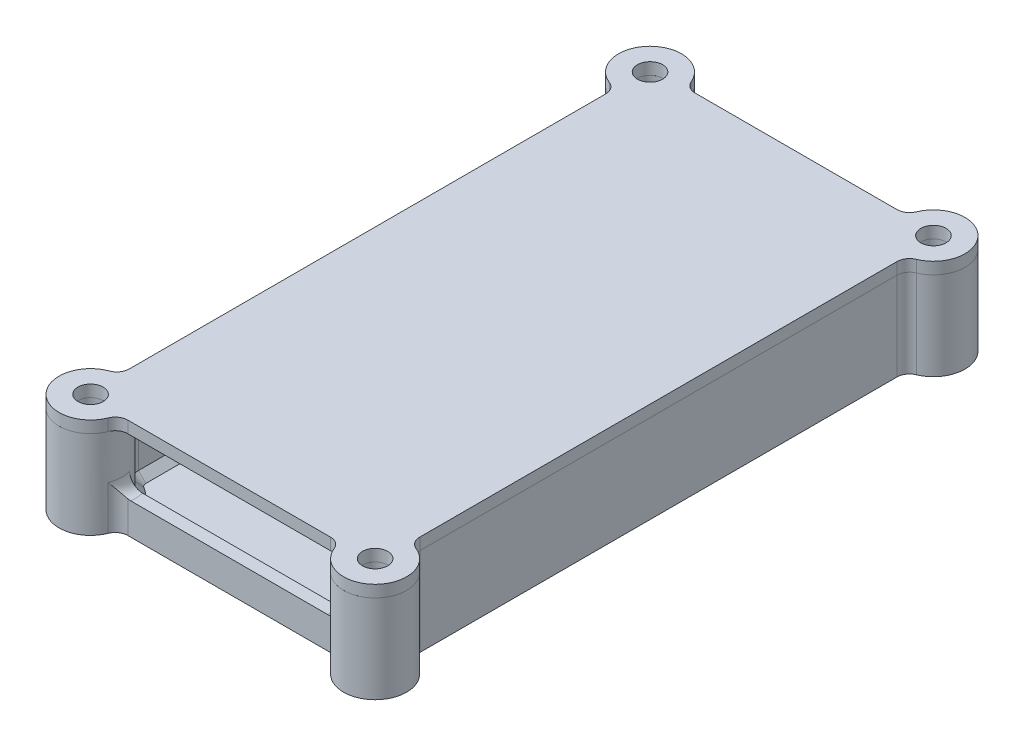
SolidWorks part; units mm, degrees
material "Nylon 101"
ref_plane "Front Plane" through (0, 0, 0) normal (0, 0, 1) x (1, 0, 0)
ref_plane "Top Plane" through (0, 0, 0) normal (0, 1, 0) x (1, 0, 0)
ref_plane "Right Plane" through (0, 0, 0) normal (1, 0, 0) x (0, 0, -1)
sketch "Sketch1" plane through (0, 0, 0) normal (0, 1, 0) x (1, 0, 0)
  line L0 (0, 76.6523) -> (0, -58.1633) construction
  line L5 (-26.67, -25.4) -> (-1.27, -25.4)
  line L6 (-26.67, -25.4) -> (-26.67, 25.4)
  line L7 (-26.67, 25.4) -> (-1.27, 25.4)
  line L8 (-1.27, -25.4) -> (-1.27, 25.4)
  line L17 (-29.21, 27.94) -> (-29.21, -27.94)
  line L18 (-29.21, -27.94) -> (29.4349, -27.94)
  line L19 (29.4349, -27.94) -> (29.4349, 27.94)
  line L20 (29.4349, 27.94) -> (-29.21, 27.94)
  line L21 (26.67, 25.4) -> (1.27, 25.4)
  line L22 (1.27, -25.4) -> (1.27, 25.4)
  line L23 (26.67, -25.4) -> (1.27, -25.4)
  line L24 (26.67, -25.4) -> (26.67, 25.4)
  line L33 (-29.21, 27.94) -> (29.4349, 27.94)
  line L34 (-29.21, -27.94) -> (29.4349, -27.94)
  line L35 (-29.21, -27.94) -> (-29.21, -38.6473)
  line L36 (-29.21, -27.94) -> (29.4349, -27.94)
  line L37 (-29.21, -45.72) -> (-26.2624, -45.72)
  line L38 (29.4349, -27.94) -> (29.4349, -38.6698)
  line L39 (-26.67, -27.94) -> (26.8949, -27.94)
  line L42 (-29.21, 0) -> (29.4349, 0) construction
  line L43 (-26.67, -27.94) -> (-26.67, -38.9562)
  line L44 (-22.6003, -43.18) -> (22.6003, -43.18)
  line L45 (26.8949, -27.94) -> (26.8949, -38.8853) construction
  line L46 (26.7789, 65.924) -> (29.4349, 68.58) construction
  line L47 (-26.67, 27.94) -> (26.67, 27.94)
  line L48 (-29.21, 27.94) -> (29.4349, 27.94)
  line L49 (-26.67, 27.94) -> (-26.67, 61.6625)
  line L54 (-26.67, -25.4) -> (-26.67, -27.94)
  line L55 (26.8949, -27.94) -> (26.67, -25.4) construction
  line L56 (26.67, 25.4) -> (26.67, 27.94)
  line L57 (-26.67, 25.4) -> (-26.67, 27.94)
  line L58 (-1.27, 25.4) -> (1.27, 25.4)
  line L59 (1.27, -25.4) -> (-1.27, -25.4)
  line L60 (-22.4513, 66.04) -> (22.4513, 66.04)
  line L61 (26.67, 27.94) -> (26.67, 61.6625)
  line L62 (-29.21, 27.94) -> (29.4349, 27.94)
  line L63 (-29.21, 27.94) -> (-29.21, 61.4019)
  line L64 (-29.21, 68.58) -> (-26.185, 68.58)
  line L65 (29.4349, 27.94) -> (29.4349, 61.4286)
  line L66 (26.8949, -43.18) -> (29.4349, -45.72) construction
  line L67 (-22.2835, 68.58) -> (22.2835, 68.58)
  line L68 (-29.21, 65.2607) -> (-29.21, 68.58)
  line L69 (26.185, 68.58) -> (29.4349, 68.58)
  line L70 (29.4349, 65.3301) -> (29.4349, 68.58)
  line L71 (26.2624, -45.72) -> (29.4349, -45.72)
  line L72 (29.4349, -42.5474) -> (29.4349, -45.72)
  line L73 (-22.3847, -45.72) -> (22.3847, -45.72)
  line L74 (-29.21, -42.4896) -> (-29.21, -45.72)
  line L75 (22.4513, 66.04) -> (26.67, 66.04) construction
  line L76 (26.67, 66.04) -> (26.67, 61.6625) construction
  line L77 (26.8949, -38.8853) -> (26.8949, -43.18) construction
  line L78 (26.8949, -43.18) -> (22.6003, -43.18) construction
  line L79 (26.67, -25.4) -> (26.67, -43.4375)
  circle A0 centre (-23.368, -17.78) radius 1.4605
  circle A1 centre (-4.6736, 16.637) radius 1.4605
  circle A2 centre (23.2664, 16.637) radius 1.4605
  circle A3 centre (4.572, -17.78) radius 1.4605
  circle A4 centre (28.575, 67.7201) radius 2.54
  circle A5 centre (-28.575, 67.7201) radius 2.54
  circle A6 centre (28.691, -44.9761) radius 2.54
  circle A7 centre (-28.691, -44.9761) radius 2.54
  circle A8 centre (28.575, 67.7201) radius 6.35
  circle A9 centre (-28.575, 67.7201) radius 6.35
  circle A10 centre (-28.691, -44.9761) radius 6.35
  circle A11 centre (28.691, -44.9761) radius 6.35
  point P0 (0, 0)
  point P1 (-26.67, 0)
  point P21 (13.97, -25.4)
  point P22 (-1.27, 0)
  point P23 (1.27, 0)
  dimension "D15" = 2.921
  dimension "D22" = 5.08
  dimension "D23" = 12.7
  dimension "D4" = 57.15
  dimension "D2" = 50.8
  dimension "D3" = 25.4
  dimension "D5" = 2.54
  dimension "D6" = 2.54
  dimension "D7" = 2.54
  dimension "D8" = 2.54
  dimension "D9" = 2.54
  dimension "D10" = 114.3
  dimension "D11" = 2.54
  dimension "D12" = 2.54
  dimension "D13" = 7.62
  dimension "D14" = 3.302
  dimension "D16" = 3.302
  dimension "D17" = 34.417
  dimension "D18" = 18.6944
  dimension "D19" = 18.6944
  dimension "D20" = 2.54
  dimension "D21" = 38.1
  dimension "D27" = 45
  dimension "D24" = 3.81
  dimension "D25" = 3.81
  dimension "D26" = 3.81
extrude "Boss-Extrude1" add sketch "Sketch1" along normal blind 17.78 contours A10 A7 | L35 A10 L43 L18 | L6 L57 L20 L17 L18 L54 | L56 L24 L55 L18 L19 L20 | A11 L38 L18 L45 | A11 A6 | L49 A9 L63 L20 | A8 L61 L20 L65 | A9 A5 | L67 A9 L60 A8 | A8 A4 | L59 L22 L58 L8
sketch "Sketch25" plane through (0, 0, 0) normal (0, 1, 0) x (1, 0, 0)
  line L0 (26.8949, -43.18) -> (22.6003, -43.18) construction
  line L1 (26.8949, -38.8853) -> (26.8949, -43.18) construction
  line L2 (26.8949, -43.18) -> (29.4349, -45.72) construction
  line L3 (29.4349, -42.5474) -> (29.4349, -45.72) construction
  line L4 (26.2624, -45.72) -> (29.4349, -45.72) construction
  line L5 (29.4349, -27.94) -> (29.4349, -38.6698) construction
  line L6 (26.8949, -27.94) -> (26.8949, -38.8853) construction
  line L7 (-29.21, -45.72) -> (-26.2624, -45.72) construction
  line L8 (-29.21, -42.4896) -> (-29.21, -45.72) construction
  line L9 (-29.21, -27.94) -> (-29.21, -38.6473) construction
  line L10 (-26.67, -27.94) -> (-26.67, -38.9562) construction
  line L11 (-22.3847, -45.72) -> (22.3847, -45.72) construction
  line L12 (-22.6003, -43.18) -> (22.6003, -43.18) construction
  line L13 (-26.67, -25.4) -> (-1.27, -25.4) construction
  line L14 (26.67, -25.4) -> (1.27, -25.4) construction
  line L15 (-29.21, -27.94) -> (29.4349, -27.94) construction
  line L16 (-29.21, 0) -> (29.4349, 0) construction
  line L17 (-26.67, -25.4) -> (-26.67, 25.4) construction
  line L18 (-1.27, -25.4) -> (-1.27, 25.4) construction
  line L19 (1.27, -25.4) -> (1.27, 25.4) construction
  line L20 (26.67, 25.4) -> (26.67, 27.94) construction
  line L21 (26.67, -25.4) -> (26.67, 25.4) construction
  line L22 (29.4349, -27.94) -> (29.4349, 27.94) construction
  line L23 (26.67, 25.4) -> (1.27, 25.4) construction
  line L24 (-29.21, 27.94) -> (-29.21, -27.94) construction
  line L25 (-26.67, 25.4) -> (-26.67, 27.94) construction
  line L26 (-26.67, 25.4) -> (-1.27, 25.4) construction
  line L27 (29.4349, 27.94) -> (-29.21, 27.94) construction
  line L28 (-29.21, 27.94) -> (-29.21, 61.4019) construction
  line L29 (-26.67, 27.94) -> (-26.67, 61.6625) construction
  line L30 (26.67, 66.04) -> (26.67, 61.6625) construction
  line L31 (22.4513, 66.04) -> (26.67, 66.04) construction
  line L32 (26.67, 27.94) -> (26.67, 61.6625) construction
  line L33 (29.4349, 27.94) -> (29.4349, 61.4286) construction
  line L34 (26.185, 68.58) -> (29.4349, 68.58) construction
  line L35 (29.4349, 65.3301) -> (29.4349, 68.58) construction
  line L36 (26.7789, 65.924) -> (29.4349, 68.58) construction
  line L37 (0, 76.6523) -> (0, -58.1633) construction
  line L38 (-22.4513, 66.04) -> (22.4513, 66.04) construction
  line L39 (-22.2835, 68.58) -> (22.2835, 68.58) construction
  line L40 (-29.21, 68.58) -> (-26.185, 68.58) construction
  line L41 (-29.21, 65.2607) -> (-29.21, 68.58) construction
  line L42 (26.8949, -43.18) -> (22.6003, -43.18) construction
  line L43 (26.8949, -38.8853) -> (26.8949, -43.18) construction
  line L44 (26.8949, -43.18) -> (29.4349, -45.72) construction
  line L45 (29.4349, -42.5474) -> (29.4349, -45.72)
  line L46 (26.2624, -45.72) -> (29.4349, -45.72)
  line L47 (29.4349, -27.94) -> (29.4349, -38.6698)
  line L48 (26.8949, -27.94) -> (26.8949, -38.8853)
  line L49 (-29.21, -45.72) -> (-26.2624, -45.72)
  line L50 (-29.21, -42.4896) -> (-29.21, -45.72)
  line L51 (-29.21, -27.94) -> (-29.21, -38.6473)
  line L52 (-26.67, -27.94) -> (-26.67, -38.9562)
  line L53 (-22.3847, -45.72) -> (22.3847, -45.72)
  line L54 (-22.6003, -43.18) -> (22.6003, -43.18)
  line L55 (-26.67, -25.4) -> (-1.27, -25.4)
  line L56 (26.67, -25.4) -> (1.27, -25.4)
  line L57 (-29.21, -27.94) -> (29.4349, -27.94)
  line L58 (-29.21, 0) -> (29.4349, 0) construction
  line L59 (-26.67, -25.4) -> (-26.67, 25.4)
  line L60 (-1.27, -25.4) -> (-1.27, 25.4)
  line L61 (1.27, -25.4) -> (1.27, 25.4)
  line L62 (26.67, 25.4) -> (26.67, 27.94)
  line L63 (26.67, -25.4) -> (26.67, 25.4)
  line L64 (29.4349, -27.94) -> (29.4349, 27.94)
  line L65 (26.67, 25.4) -> (1.27, 25.4)
  line L66 (-29.21, 27.94) -> (-29.21, -27.94)
  line L67 (-26.67, 25.4) -> (-26.67, 27.94)
  line L68 (-26.67, 25.4) -> (-1.27, 25.4)
  line L69 (29.4349, 27.94) -> (-29.21, 27.94)
  line L70 (-29.21, 27.94) -> (-29.21, 61.4019)
  line L71 (-26.67, 27.94) -> (-26.67, 61.6625)
  line L72 (26.67, 66.04) -> (26.67, 61.6625) construction
  line L73 (22.4513, 66.04) -> (26.67, 66.04) construction
  line L74 (26.67, 27.94) -> (26.67, 61.6625)
  line L75 (29.4349, 27.94) -> (29.4349, 61.4286)
  line L76 (26.185, 68.58) -> (29.4349, 68.58) construction
  line L77 (29.4349, 65.3301) -> (29.4349, 68.58) construction
  line L78 (26.7789, 65.924) -> (29.4349, 68.58) construction
  line L79 (0, 76.6523) -> (0, -58.1633) construction
  line L80 (-22.4513, 66.04) -> (22.4513, 66.04)
  line L81 (-22.2835, 68.58) -> (22.2835, 68.58)
  line L82 (-29.21, 68.58) -> (-26.185, 68.58)
  line L83 (-29.21, 65.2607) -> (-29.21, 68.58)
  circle A0 centre (28.691, -44.9761) radius 2.54 construction
  circle A1 centre (28.691, -44.9761) radius 6.35 construction
  circle A2 centre (-28.691, -44.9761) radius 2.54 construction
  circle A3 centre (-28.691, -44.9761) radius 6.35 construction
  circle A4 centre (23.2664, 16.637) radius 1.4605 construction
  circle A5 centre (-23.368, -17.78) radius 1.4605 construction
  circle A6 centre (-4.6736, 16.637) radius 1.4605 construction
  circle A7 centre (28.575, 67.7201) radius 2.54 construction
  circle A8 centre (28.575, 67.7201) radius 6.35 construction
  circle A9 centre (-28.575, 67.7201) radius 6.35 construction
  circle A10 centre (28.691, -44.9761) radius 2.54
  circle A11 centre (28.691, -44.9761) radius 6.35
  circle A12 centre (-28.691, -44.9761) radius 2.54
  circle A13 centre (-28.691, -44.9761) radius 6.35
  circle A14 centre (23.2664, 16.637) radius 1.4605
  circle A15 centre (-23.368, -17.78) radius 1.4605
  circle A16 centre (-4.6736, 16.637) radius 1.4605
  circle A17 centre (28.575, 67.7201) radius 2.54
  circle A18 centre (28.575, 67.7201) radius 6.35
  circle A19 centre (-28.575, 67.7201) radius 6.35
  circle A20 centre (4.572, -17.78) radius 1.4605 construction
  circle A21 centre (-28.575, 67.7201) radius 2.54 construction
  circle A22 centre (4.572, -17.78) radius 1.4605
  circle A23 centre (-28.575, 67.7201) radius 2.54
  point P0 (-26.67, 61.6625)
sketch "Sketch16" plane through (0, 0, 0) normal (0, 1, 0) x (1, 0, 0)
  line L0 (0, 63.9928) -> (0, -58.1633) construction
  line L5 (-26.67, -25.4) -> (-1.27, -25.4)
  line L6 (-26.67, -25.4) -> (-26.67, 25.4)
  line L7 (-26.67, 25.4) -> (-1.27, 25.4)
  line L8 (-1.27, -25.4) -> (-1.27, 25.4)
  line L17 (-29.21, 27.94) -> (-29.21, -27.94)
  line L18 (-29.21, -27.94) -> (29.21, -27.94)
  line L19 (29.21, -27.94) -> (29.21, 27.94)
  line L20 (29.21, 27.94) -> (-29.21, 27.94)
  line L21 (26.67, 25.4) -> (1.27, 25.4)
  line L22 (1.27, -25.4) -> (1.27, 25.4)
  line L23 (26.67, -25.4) -> (1.27, -25.4)
  line L24 (26.67, -25.4) -> (26.67, 25.4)
  line L33 (-29.21, 27.94) -> (29.21, 27.94)
  line L34 (-29.21, -27.94) -> (29.21, -27.94)
  line L35 (-29.21, -27.94) -> (-29.21, -43.18)
  line L36 (-29.21, -27.94) -> (29.21, -27.94)
  line L37 (-29.21, -43.18) -> (29.21, -43.18)
  line L38 (29.21, -27.94) -> (29.21, -43.18)
  line L39 (-26.67, -27.94) -> (26.67, -27.94)
  line L42 (-29.21, 0) -> (29.21, 0) construction
  line L43 (-26.67, -27.94) -> (-26.67, -40.64)
  line L44 (-26.67, -40.64) -> (26.67, -40.64)
  line L45 (26.67, -27.94) -> (26.67, -40.64)
  line L46 (-29.21, 43.18) -> (29.21, 43.18)
  line L47 (29.21, 27.94) -> (29.21, 43.18)
  line L48 (-29.21, 27.94) -> (29.21, 27.94)
  line L49 (-29.21, 27.94) -> (-29.21, 43.18)
  line L50 (-26.67, 40.64) -> (26.67, 40.64)
  line L51 (26.67, 27.94) -> (26.67, 40.64)
  line L52 (-26.67, 27.94) -> (26.67, 27.94)
  line L53 (-26.67, 27.94) -> (-26.67, 40.64)
  line L54 (-26.67, -25.4) -> (-26.67, -27.94)
  line L55 (26.67, -27.94) -> (26.67, -25.4)
  line L56 (26.67, 25.4) -> (26.67, 27.94)
  line L57 (-26.67, 25.4) -> (-26.67, 27.94)
  line L58 (-1.27, 25.4) -> (1.27, 25.4)
  line L59 (1.27, -25.4) -> (-1.27, -25.4)
  circle A0 centre (-23.368, -17.78) radius 1.4605
  circle A1 centre (-4.6736, 16.637) radius 1.4605
  circle A2 centre (23.2664, 16.637) radius 1.4605
  circle A3 centre (4.572, -17.78) radius 1.4605
  point P0 (0, 0)
  point P1 (-26.67, 0)
  point P19 (26.67, 0)
  point P21 (13.97, -25.4)
  point P22 (-1.27, 0)
  point P23 (1.27, 0)
  point P44 (0, -1.5571)
  dimension "D15" = 2.921
  dimension "D2" = 50.8
  dimension "D3" = 25.4
  dimension "D4" = 2.54
  dimension "D5" = 2.54
  dimension "D6" = 2.54
  dimension "D7" = 2.54
  dimension "D8" = 2.54
  dimension "D9" = 2.54
  dimension "D10" = 12.7
  dimension "D11" = 2.54
  dimension "D12" = 2.54
  dimension "D13" = 7.62
  dimension "D14" = 3.302
  dimension "D16" = 3.302
  dimension "D17" = 34.417
  dimension "D18" = 18.6944
  dimension "D19" = 18.6944
sketch "Sketch17" plane through (0, 0, 0) normal (0, 1, 0) x (1, 0, 0)
  line L0 (0, 63.9928) -> (0, -58.1633) construction
  line L5 (-26.67, -25.4) -> (-1.27, -25.4)
  line L6 (-26.67, -25.4) -> (-26.67, 25.4)
  line L7 (-26.67, 25.4) -> (-1.27, 25.4)
  line L8 (-1.27, -25.4) -> (-1.27, 25.4)
  line L17 (-29.21, 27.94) -> (-29.21, -27.94)
  line L18 (-29.21, -27.94) -> (29.21, -27.94)
  line L19 (29.21, -27.94) -> (29.21, 27.94)
  line L20 (29.21, 27.94) -> (-29.21, 27.94)
  line L21 (26.67, 25.4) -> (1.27, 25.4)
  line L22 (1.27, -25.4) -> (1.27, 25.4)
  line L23 (26.67, -25.4) -> (1.27, -25.4)
  line L24 (26.67, -25.4) -> (26.67, 25.4)
  line L33 (-29.21, 27.94) -> (29.21, 27.94)
  line L34 (-29.21, -27.94) -> (29.21, -27.94)
  line L35 (-29.21, -27.94) -> (-29.21, -43.18)
  line L36 (-29.21, -27.94) -> (29.21, -27.94)
  line L37 (-29.21, -43.18) -> (29.21, -43.18)
  line L38 (29.21, -27.94) -> (29.21, -43.18)
  line L39 (-26.67, -27.94) -> (26.67, -27.94)
  line L42 (-29.21, 0) -> (29.21, 0) construction
  line L43 (-26.67, -27.94) -> (-26.67, -40.64)
  line L44 (-26.67, -40.64) -> (26.67, -40.64)
  line L45 (26.67, -27.94) -> (26.67, -40.64)
  line L46 (-29.21, 43.18) -> (29.21, 43.18)
  line L47 (29.21, 27.94) -> (29.21, 43.18)
  line L48 (-29.21, 27.94) -> (29.21, 27.94)
  line L49 (-29.21, 27.94) -> (-29.21, 43.18)
  line L50 (-26.67, 40.64) -> (26.67, 40.64)
  line L51 (26.67, 27.94) -> (26.67, 40.64)
  line L52 (-26.67, 27.94) -> (26.67, 27.94)
  line L53 (-26.67, 27.94) -> (-26.67, 40.64)
  line L54 (-26.67, -25.4) -> (-26.67, -27.94)
  line L55 (26.67, -27.94) -> (26.67, -25.4)
  line L56 (26.67, 25.4) -> (26.67, 27.94)
  line L57 (-26.67, 25.4) -> (-26.67, 27.94)
  line L58 (-1.27, 25.4) -> (1.27, 25.4)
  line L59 (1.27, -25.4) -> (-1.27, -25.4)
  circle A0 centre (-23.368, -17.78) radius 1.4605
  circle A1 centre (-4.6736, 16.637) radius 1.4605
  circle A2 centre (23.622, 16.637) radius 1.4605
  circle A3 centre (4.572, -17.78) radius 1.4605
  point P0 (0, 0)
  point P1 (-26.67, 0)
  point P19 (26.67, 0)
  point P21 (13.97, -25.4)
  point P22 (-1.27, 0)
  point P23 (1.27, 0)
  dimension "D15" = 2.921
  dimension "D2" = 50.8
  dimension "D3" = 25.4
  dimension "D4" = 2.54
  dimension "D5" = 2.54
  dimension "D6" = 2.54
  dimension "D7" = 2.54
  dimension "D8" = 2.54
  dimension "D9" = 2.54
  dimension "D10" = 12.7
  dimension "D11" = 2.54
  dimension "D12" = 2.54
  dimension "D13" = 7.62
  dimension "D14" = 3.302
  dimension "D16" = 3.302
  dimension "D17" = 34.417
  dimension "D18" = 18.6944
  dimension "D19" = 19.05
extrude "Boss-Extrude10" add sketch "Sketch25" along normal blind 2.54 contours L68 L59 L55 L60 A16 A15 | L63 L65 L61 L56 A22 A14 | A19 L71 L69 L74 A18 L80 | A13 L54 A11 L48 L57 L52
extrude "Boss-Extrude8" add sketch "Sketch16" along normal blind 7.62 contours A1 | A0 | A3 | A2
extrude "Boss-Extrude9" add sketch "Sketch17" along normal blind 10.16 contours L23 L59 L5 L54 L36 L55 | L7 L58 L21 L56 L48 L57 | L20
sketch "Sketch27" plane through (0, 0, 0) normal (0, 1, 0) x (1, 0, 0)
  line L0 (0, 76.6523) -> (0, -58.1633) construction
  line L5 (-26.67, -25.4) -> (-1.27, -25.4)
  line L6 (-26.67, -25.4) -> (-26.67, 25.4)
  line L7 (-26.67, 25.4) -> (-1.27, 25.4)
  line L8 (-1.27, -25.4) -> (-1.27, 25.4)
  line L17 (-29.21, 27.94) -> (-29.21, -27.94)
  line L18 (-29.21, -27.94) -> (29.4349, -27.94)
  line L19 (29.4349, -27.94) -> (29.4349, 27.94)
  line L20 (29.4349, 27.94) -> (-29.21, 27.94)
  line L21 (26.67, 25.4) -> (1.27, 25.4)
  line L22 (1.27, -25.4) -> (1.27, 25.4)
  line L23 (26.67, -25.4) -> (1.27, -25.4)
  line L24 (26.67, -25.4) -> (26.67, 25.4)
  line L33 (-29.21, 27.94) -> (29.4349, 27.94)
  line L34 (-29.21, -27.94) -> (29.4349, -27.94)
  line L35 (-29.21, -27.94) -> (-29.21, -38.6473)
  line L36 (-29.21, -27.94) -> (29.4349, -27.94)
  line L37 (-29.21, -45.72) -> (-26.2624, -45.72)
  line L38 (29.4349, -27.94) -> (29.4349, -38.6698)
  line L39 (-26.67, -27.94) -> (26.8949, -27.94)
  line L42 (-29.21, 0) -> (29.4349, 0) construction
  line L43 (-26.67, -27.94) -> (-26.67, -38.9562)
  line L44 (-22.6003, -43.18) -> (22.6003, -43.18)
  line L45 (26.8949, -27.94) -> (26.8949, -38.8853) construction
  line L46 (26.7789, 65.924) -> (29.4349, 68.58) construction
  line L47 (-26.67, 27.94) -> (26.67, 27.94)
  line L48 (-29.21, 27.94) -> (29.4349, 27.94)
  line L49 (-26.67, 27.94) -> (-26.67, 61.6625)
  line L54 (-26.67, -25.4) -> (-26.67, -27.94)
  line L55 (26.8949, -27.94) -> (26.67, -25.4) construction
  line L56 (26.67, 25.4) -> (26.67, 27.94)
  line L57 (-26.67, 25.4) -> (-26.67, 27.94)
  line L58 (-1.27, 25.4) -> (1.27, 25.4)
  line L59 (1.27, -25.4) -> (-1.27, -25.4)
  line L60 (-22.4513, 66.04) -> (22.4513, 66.04)
  line L61 (26.67, 27.94) -> (26.67, 61.6625)
  line L62 (-29.21, 27.94) -> (29.4349, 27.94)
  line L63 (-29.21, 27.94) -> (-29.21, 61.4019)
  line L64 (-29.21, 68.58) -> (-26.185, 68.58)
  line L65 (29.4349, 27.94) -> (29.4349, 61.4286)
  line L66 (26.8949, -43.18) -> (29.4349, -45.72) construction
  line L67 (-22.2835, 68.58) -> (22.2835, 68.58)
  line L68 (-29.21, 65.2607) -> (-29.21, 68.58)
  line L69 (26.185, 68.58) -> (29.4349, 68.58)
  line L70 (29.4349, 65.3301) -> (29.4349, 68.58)
  line L71 (26.2624, -45.72) -> (29.4349, -45.72)
  line L72 (29.4349, -42.5474) -> (29.4349, -45.72)
  line L73 (-22.3847, -45.72) -> (22.3847, -45.72)
  line L74 (-29.21, -42.4896) -> (-29.21, -45.72)
  line L75 (22.4513, 66.04) -> (26.67, 66.04) construction
  line L76 (26.67, 66.04) -> (26.67, 61.6625) construction
  line L77 (26.8949, -38.8853) -> (26.8949, -43.18) construction
  line L78 (26.8949, -43.18) -> (22.6003, -43.18) construction
  line L79 (26.67, -25.4) -> (26.67, -43.4375)
  circle A0 centre (-23.368, -17.78) radius 1.4605
  circle A1 centre (-4.6736, 16.637) radius 1.4605
  circle A2 centre (23.2664, 16.637) radius 1.4605
  circle A3 centre (4.572, -17.78) radius 1.4605
  circle A4 centre (28.575, 67.7201) radius 2.54
  circle A5 centre (-28.575, 67.7201) radius 2.54
  circle A6 centre (28.691, -44.9761) radius 2.54
  circle A7 centre (-28.691, -44.9761) radius 2.54
  circle A8 centre (28.575, 67.7201) radius 6.35
  circle A9 centre (-28.575, 67.7201) radius 6.35
  circle A10 centre (-28.691, -44.9761) radius 6.35
  circle A11 centre (28.691, -44.9761) radius 6.35
  point P0 (0, 0)
extrude "Boss-Extrude11" add sketch "Sketch27" along normal blind 6.35 contours A11 L44 A10 L73
sketch "Sketch20" plane through (0, 0, -68.58) normal (0, 0, -1) x (-1, 0, 0)
  line L5 (-12.7, 17.78) -> (12.7, 17.78)
  line L6 (-12.7, 17.78) -> (-12.7, 6.35)
  line L7 (-12.7, 6.35) -> (12.7, 6.35)
  line L8 (12.7, 17.78) -> (12.7, 6.35)
  line L10 (22.2835, 17.78) -> (-22.2835, 17.78) construction
  point P4 (0, 17.78)
  point P5 (0, 17.78)
  dimension "D1" = 25.4
  dimension "D2" = 11.43
extrude "Cut-Extrude7" cut sketch "Sketch20" against normal up to next
fillet "Fillet1" radius 2.54 21 edges at (22.3637, 6.35, 44.4391) (22.3847, 3.175, 45.72) (22.6003, 4.445, 43.18) (-22.3847, 3.175, 45.72) (-22.3637, 6.35, 44.4391) (-12.7, 6.35, -67.31) (-12.7, 17.78, -67.31) (12.7, 17.78, -67.31) (12.7, 6.35, -67.31) (26.67, 10.16, -61.6625) (22.4513, 10.16, -66.04) (-22.4513, 10.16, -66.04) (-26.67, 10.16, -61.6625) (-26.67, 10.16, 38.9562) (-29.21, 8.89, 38.6473) (-29.21, 8.89, -61.4019) (-22.2835, 8.89, -68.58) (22.2835, 8.89, -68.58) (29.4349, 8.89, -61.4286) (29.4349, 8.89, 38.6698) (26.67, 10.16, 38.9562)
chamfer "Chamfer1" distance 1.5 angle 45 25 edges at (-26.67, 2.54, -43.9805) (0, 2.54, -27.94) (26.67, 2.54, -43.9805) (-23.6723, 2.54, 41.0857) (0, 2.54, 27.94) (-26.67, 2.54, 32.6426) (-0.8351, 2.54, 43.18) (-26.67, 10.16, 26.67) (26.67, 10.16, 26.67) (-26.67, 10.16, -26.67) (26.67, 10.16, -26.67) (24.1357, 2.54, 40.552) (26.67, 2.54, 32.6426) (22.2156, 2.54, 42.8307) (26.3393, 2.54, 38.5986) (-26.3393, 2.54, 38.5986) (0, 2.54, -66.04) (24.0203, 2.54, -63.2955) (-24.0203, 2.54, -63.2955) (-26.3297, 2.54, -61.2911) (-22.0522, 2.54, -65.6811) (26.3297, 2.54, -61.2911) (22.0522, 2.54, -65.6811) (0, 17.78, 25.4) (0, 17.78, -25.4)
chamfer "Chamfer2" distance 0.4 angle 45 12 edges at (13.97, 2.54, 25.4) (1.27, 2.54, 0) (13.97, 2.54, -25.4) (26.67, 2.54, 0) (23.2664, 2.54, -15.1765) (4.572, 2.54, 19.2405) (-1.27, 2.54, 0) (-13.97, 2.54, 25.4) (-26.67, 2.54, 0) (-13.97, 2.54, -25.4) (-23.368, 2.54, 19.2405) (-4.6736, 2.54, -15.1765)
sketch "Sketch28" plane through (0, 17.78, 0) normal (0, 1, 0) x (1, 0, 0)
  line L4 (-20.4298, -45.72) -> (20.4298, -45.72)
  line L5 (-29.21, 59.4163) -> (-29.21, -36.6289)
  line L6 (20.3608, 68.58) -> (-20.3608, 68.58)
  line L7 (29.4349, -36.7148) -> (29.4349, 59.5059)
  line L9 (-29.21, 59.4163) -> (-29.21, -36.6289)
  line L10 (20.3608, 68.58) -> (-20.3608, 68.58)
  line L11 (29.4349, -36.7148) -> (29.4349, 59.5059)
  line L12 (-20.4298, -45.72) -> (20.4298, -45.72)
  circle A0 centre (28.691, -44.9761) radius 2.54 construction
  circle A1 centre (-28.691, -44.9761) radius 2.54 construction
  circle A2 centre (-28.575, 67.7201) radius 2.54 construction
  circle A3 centre (28.575, 67.7201) radius 2.54 construction
  arc A4 (22.7901, -47.3217) -> (31.0367, -39.0752) centre (28.691, -44.9761) ccw
  arc A5 (-30.876, -39.0138) -> (-22.7901, -47.3217) centre (-28.691, -44.9761) ccw
  arc A6 (-22.7077, 70.1486) -> (-30.8429, 61.7888) centre (-28.575, 67.7201) ccw
  arc A8 (22.7901, -47.3217) -> (31.0367, -39.0752) centre (28.691, -44.9761) ccw
  arc A9 (-30.876, -39.0138) -> (-22.7901, -47.3217) centre (-28.691, -44.9761) ccw
  circle A12 centre (28.691, -44.9761) radius 2.54
  circle A13 centre (-28.691, -44.9761) radius 2.54
  circle A14 centre (-28.575, 67.7201) radius 2.54
  circle A15 centre (28.575, 67.7201) radius 2.54
  arc A28 (-22.7077, 70.1486) -> (-30.8429, 61.7888) centre (-28.575, 67.7201) ccw
  arc A32 (-30.876, -39.0138) -> (-29.21, -36.6289) centre (-31.75, -36.6289) ccw
  arc A33 (-30.876, -39.0138) -> (-29.21, -36.6289) centre (-31.75, -36.6289) ccw
  arc A34 (-29.21, 59.4163) -> (-30.8429, 61.7888) centre (-31.75, 59.4163) ccw
  arc A35 (-29.21, 59.4163) -> (-30.8429, 61.7888) centre (-31.75, 59.4163) ccw
  arc A36 (-22.7077, 70.1486) -> (-20.3608, 68.58) centre (-20.3608, 71.12) ccw
  arc A37 (-22.7077, 70.1486) -> (-20.3608, 68.58) centre (-20.3608, 71.12) ccw
  arc A38 (20.3608, 68.58) -> (22.7077, 70.1486) centre (20.3608, 71.12) ccw
  arc A39 (20.3608, 68.58) -> (22.7077, 70.1486) centre (20.3608, 71.12) ccw
  arc A40 (31.0035, 61.8528) -> (29.4349, 59.5059) centre (31.9749, 59.5059) ccw
  arc A41 (31.0035, 61.8528) -> (29.4349, 59.5059) centre (31.9749, 59.5059) ccw
  arc A42 (29.4349, -36.7148) -> (31.0367, -39.0752) centre (31.9749, -36.7148) ccw
  arc A43 (29.4349, -36.7148) -> (31.0367, -39.0752) centre (31.9749, -36.7148) ccw
  arc A44 (31.0035, 61.8528) -> (22.7077, 70.1486) centre (28.575, 67.7201) ccw
  arc A45 (31.0035, 61.8528) -> (22.7077, 70.1486) centre (28.575, 67.7201) ccw
  arc A47 (22.7901, -47.3217) -> (20.4298, -45.72) centre (20.4298, -48.26) ccw
  arc A49 (22.7901, -47.3217) -> (20.4298, -45.72) centre (20.4298, -48.26) ccw
  arc A51 (-20.4298, -45.72) -> (-22.7901, -47.3217) centre (-20.4298, -48.26) ccw
  arc A52 (-20.4298, -45.72) -> (-22.7901, -47.3217) centre (-20.4298, -48.26) ccw
  dimension "D1" = 0
extrude "Boss-Extrude12" add sketch "Sketch28" along normal blind 2.3813 separate body
